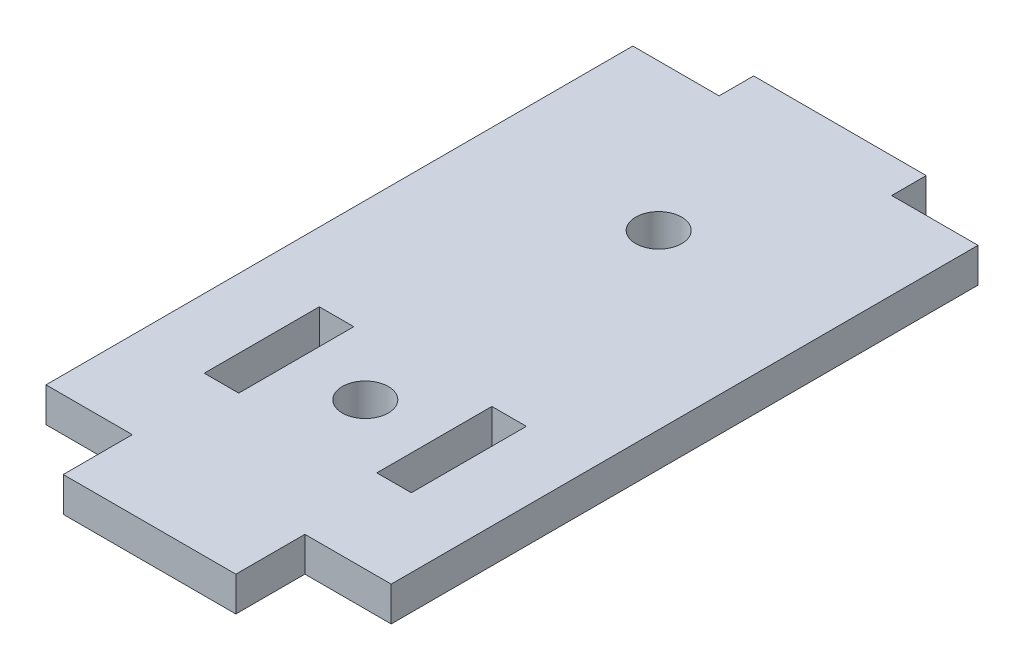
SolidWorks part; units mm, degrees
ref_plane "Front Plane" through (0, 0, 0) normal (0, 0, 1) x (1, 0, 0)
ref_plane "Top Plane" through (0, 0, 0) normal (0, 1, 0) x (1, 0, 0)
ref_plane "Right Plane" through (0, 0, 0) normal (1, 0, 0) x (0, 0, -1)
sketch "Sketch1" plane through (0, 0, 0) normal (0, 1, 0) x (1, 0, 0)
  line L0 (0, 25.5) -> (0, 0)
  line L1 (15, -25.5) -> (-15, -25.5)
  line L2 (15, -25.5) -> (15, 25.5)
  line L3 (15, 25.5) -> (-15, 25.5)
  line L4 (-15, -25.5) -> (-15, 25.5)
  line L5 (15, -25.5) -> (-15, 25.5) construction
  line L6 (15, 25.5) -> (-15, -25.5) construction
  line L15 (0, -25.5) -> (-7.5, -25.5)
  line L16 (0, -25.5) -> (0, -31.5)
  line L17 (0, -31.5) -> (-7.5, -31.5)
  line L18 (-7.5, -25.5) -> (-7.5, -31.5)
  line L19 (0, -25.5) -> (7.5, -25.5)
  line L20 (0, -25.5) -> (0, -31.5)
  line L21 (0, -31.5) -> (7.5, -31.5)
  line L22 (7.5, -25.5) -> (7.5, -31.5)
  line L23 (0, 0) -> (0, -25.5)
  line L24 (0, -12.75) -> (15, -12.75)
  line L25 (0, -12.75) -> (-15, -12.75)
  line L26 (6, -17.75) -> (9, -17.75)
  line L27 (6, -17.75) -> (6, -7.75)
  line L28 (6, -7.75) -> (9, -7.75)
  line L29 (9, -17.75) -> (9, -7.75)
  line L30 (6, -17.75) -> (9, -7.75) construction
  line L31 (6, -7.75) -> (9, -17.75) construction
  line L33 (-6, -17.75) -> (-9, -17.75)
  line L34 (-6, -17.75) -> (-6, -7.75)
  line L35 (-6, -7.75) -> (-9, -7.75)
  line L36 (-9, -17.75) -> (-9, -7.75)
  line L37 (-6, -17.75) -> (-9, -7.75) construction
  line L38 (-6, -7.75) -> (-9, -17.75) construction
  line L39 (7.5, 28.5) -> (-7.5, 28.5)
  line L40 (7.5, 28.5) -> (7.5, 25.5)
  line L41 (7.5, 25.5) -> (-7.5, 25.5)
  line L42 (-7.5, 28.5) -> (-7.5, 25.5)
  circle A0 centre (0, 12.75) radius 2
  circle A1 centre (0, -12.75) radius 2
  point P0 (0, 0)
  point P25 (7.5, -12.75)
  point P31 (-7.5, -12.75)
  dimension "D2" = 2
  dimension "D4" = 2
  dimension "D1" = 25.5
  dimension "D3" = 25.5
  dimension "D5" = 15
  dimension "D6" = 15
extrude "Boss-Extrude1" add sketch "Sketch1" along normal blind 3
